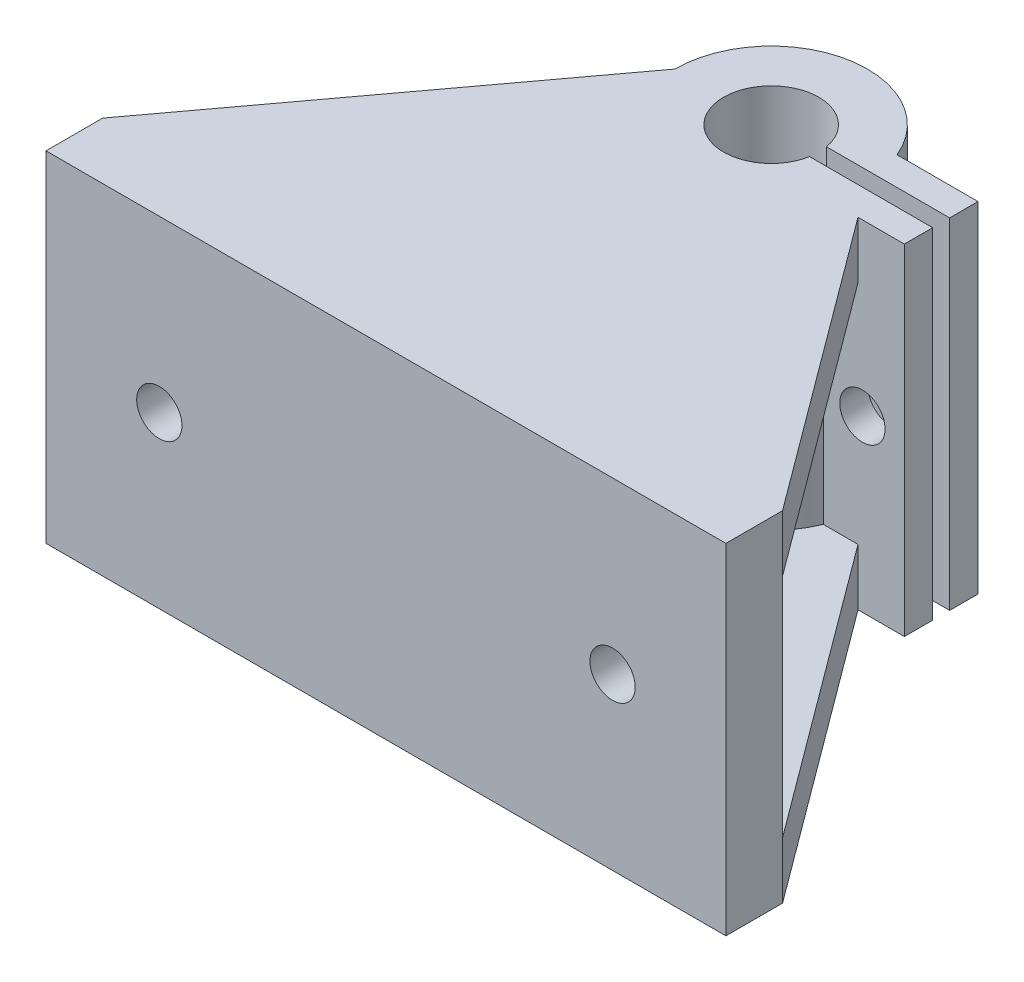
SolidWorks part; units mm, degrees
ref_plane "Płaszczyzna przednia" through (0, 0, 0) normal (0, 0, 1) x (1, 0, 0)
ref_plane "Płaszczyzna górna" through (0, 0, 0) normal (0, 1, 0) x (1, 0, 0)
ref_plane "Płaszczyzna prawa" through (0, 0, 0) normal (1, 0, 0) x (0, 0, -1)
sketch "Szkic1" plane through (0, 0, 0) normal (0, 1, 0) x (1, 0, 0)
  line L1 (-30, 0) -> (30, 0)
  line L2 (-30, 0) -> (-30, 5)
  line L3 (-30, 5) -> (30, 5)
  line L4 (30, 0) -> (30, 5)
  circle A0 centre (0, 34) radius 4.2
  circle A1 centre (0, 34) radius 8.5
  point P5 (0, 0)
extrude "Dodanie-wyciągnięcie1" add sketch "Szkic1" along normal blind 30
sketch "Szkic2" plane through (0, 0, 0) normal (0, -1, 0) x (1, 0, 0)
  line L5 (30, -5) -> (8.5, -34)
  line L6 (8.5, -34) -> (0, -25.5)
  line L7 (0, -25.5) -> (-8.5, -34)
  line L8 (-8.5, -34) -> (-30, -5)
  line L9 (-30, -5) -> (30, -5)
  circle A1 centre (0, -34) radius 8.5 construction
extrude "Dodanie-wyciągnięcie2" add sketch "Szkic2" against normal blind 5
sketch "Szkic3" plane through (0, 30, 0) normal (0, 1, 0) x (1, 0, 0)
  line L0 (30, 5) -> (-30, 5) construction
  line L1 (-3, 5) -> (3, 5)
  line L2 (-3, 5) -> (-3, 27)
  line L3 (-3, 27) -> (3, 27)
  line L4 (3, 5) -> (3, 27)
extrude "Dodanie-wyciągnięcie3" add sketch "Szkic3" against normal blind 26
sketch "Szkic4" plane through (0, 30, 0) normal (0, 1, 0) x (1, 0, 0)
  line L2 (0, 26.8242) -> (8.5, 34)
  line L3 (8.5, 34) -> (30, 5)
  line L4 (30, 5) -> (-30, 5)
  line L5 (0, 26.8242) -> (-8.5, 34)
  line L6 (-8.5, 34) -> (-30, 5)
  arc A0 (3, 26.047) -> (-3, 26.047) centre (0, 34) ccw construction
extrude "Dodanie-wyciągnięcie4" add sketch "Szkic4" against normal blind 5
sketch "Szkic5" plane through (0, 0, 0) normal (0, 0, 1) x (1, 0, 0)
  circle A0 centre (-20, 15) radius 2
  circle A1 centre (20, 15) radius 2
extrude "Wytnij-wyciągnięcie1" cut sketch "Szkic5" against normal up to next
sketch "Szkic6" plane through (0, 30, 0) normal (0, 1, 0) x (1, 0, 0)
  line L1 (0, 33.25) -> (10.271, 33.25)
  line L2 (0, 33.25) -> (0, 34.75)
  line L3 (0, 34.75) -> (10.271, 34.75)
  line L4 (10.271, 33.25) -> (10.271, 34.75)
extrude "Wytnij-wyciągnięcie2" cut sketch "Szkic6" against normal up to next
sketch "Szkic7" plane through (0, 30, 0) normal (0, 1, 0) x (1, 0, 0)
  line L0 (4.1325, 33.25) -> (9.056, 33.25) construction
  line L1 (5.7504, 33.25) -> (15, 33.25)
  line L2 (5.7504, 33.25) -> (5.7504, 30.75)
  line L3 (5.7504, 30.75) -> (15, 30.75)
  line L4 (15, 33.25) -> (15, 30.75)
  line L5 (8.4668, 34.75) -> (4.1325, 34.75) construction
  line L6 (5.7504, 34.75) -> (15, 34.75)
  line L7 (5.7504, 34.75) -> (5.7504, 37.25)
  line L8 (5.7504, 37.25) -> (15, 37.25)
  line L9 (15, 34.75) -> (15, 37.25)
extrude "Dodanie-wyciągnięcie5" add sketch "Szkic7" against normal blind 30
sketch "Szkic8" plane through (0, 0, -37.25) normal (0, 0, -1) x (-1, 0, 0)
  circle A0 centre (-11.3, 15) radius 2
extrude "Wytnij-wyciągnięcie3" cut sketch "Szkic8" against normal blind 30
